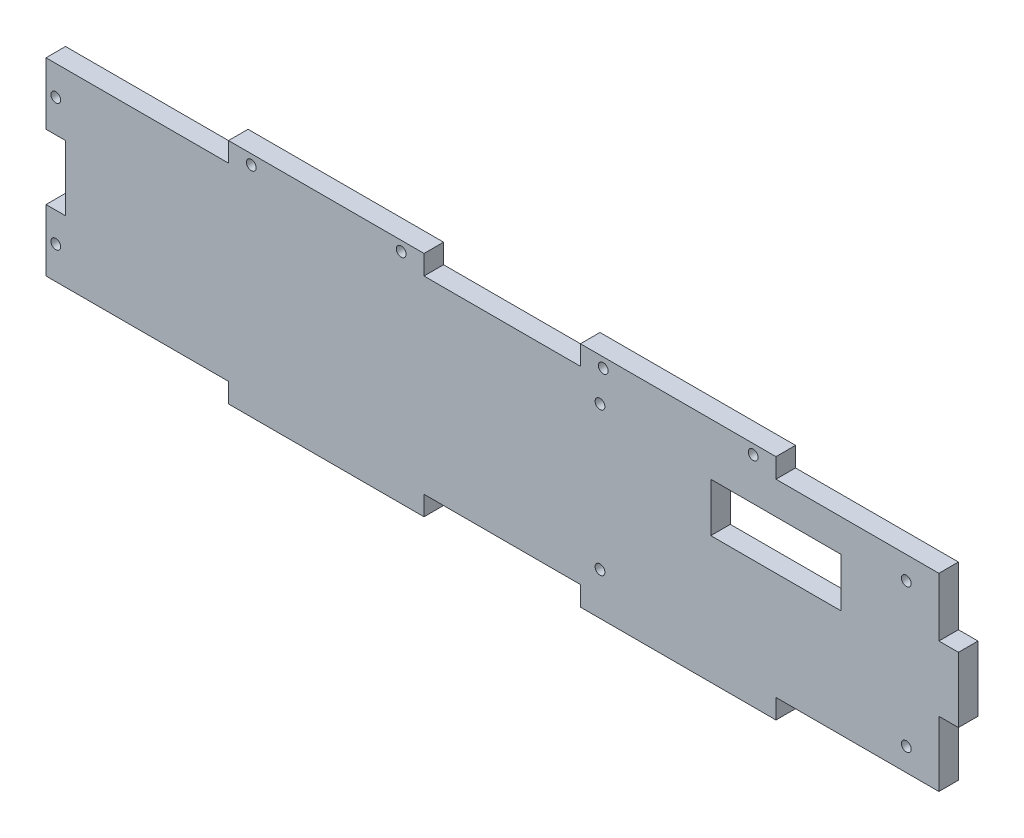
SolidWorks part; units mm, degrees
ref_plane "Plan de face" through (0, 0, 0) normal (0, 0, 1) x (1, 0, 0)
ref_plane "Plan de dessus" through (0, 0, 0) normal (0, 1, 0) x (1, 0, 0)
ref_plane "Plan de droite" through (0, 0, 0) normal (1, 0, 0) x (0, 0, -1)
sketch "Esquisse1" plane through (0, 0, 0) normal (0, 0, 1) x (1, 0, 0)
  line L1 (0, 0) -> (-268, 0)
  line L2 (0, 0) -> (0, 70)
  line L3 (0, 70) -> (-268, 70)
  line L4 (-268, 0) -> (-268, 70)
  dimension "D1" = 70
  dimension "D2" = 268
extrude "Boss.-Extru.1" add sketch "Esquisse1" along normal blind 6
sketch "Esquisse2" plane through (0, 0, 6) normal (0, 0, 1) x (1, 0, 0)
  line L0 (-268, 0) -> (0, 0) construction
  line L1 (-268, 0) -> (-218, 0)
  line L2 (-268, 0) -> (-268, 6)
  line L3 (-268, 6) -> (-218, 6)
  line L4 (-218, 0) -> (-218, 6)
  line L5 (0, 0) -> (-50, 0)
  line L6 (0, 0) -> (0, 6)
  line L7 (0, 6) -> (-50, 6)
  line L8 (-50, 0) -> (-50, 6)
  line L9 (-158, 0) -> (-110, 0)
  line L10 (-158, 0) -> (-158, 6)
  line L11 (-158, 6) -> (-110, 6)
  line L12 (-110, 0) -> (-110, 6)
  line L13 (0, 70) -> (-268, 70) construction
  line L14 (-268, 70) -> (-218, 70)
  line L15 (-268, 70) -> (-268, 64)
  line L16 (-268, 64) -> (-218, 64)
  line L17 (-218, 70) -> (-218, 64)
  line L18 (-158, 70) -> (-110, 70)
  line L19 (-158, 70) -> (-158, 64)
  line L20 (-158, 64) -> (-110, 64)
  line L21 (-110, 70) -> (-110, 64)
  line L23 (0, 70) -> (-50, 70)
  line L24 (0, 70) -> (0, 64)
  line L25 (0, 64) -> (-50, 64)
  line L26 (-50, 70) -> (-50, 64)
  dimension "D1" = 6
  dimension "D2" = 6
  dimension "D3" = 6
  dimension "D4" = 50
  dimension "D5" = 60
  dimension "D6" = 60
  dimension "D7" = 50
  dimension "D8" = 6
  dimension "D9" = 6
  dimension "D10" = 6
  dimension "D11" = 50
  dimension "D12" = 60
  dimension "D13" = 50
  dimension "D14" = 60
extrude "Enlèv. mat.-Extru.1" cut sketch "Esquisse2" against normal through all
sketch "Esquisse3" plane through (0, 0, 0) normal (1, 0, 0) x (0, 0, -1)
  line L0 (-6, 6) -> (-6, 64) construction
  line L1 (-6, 46) -> (0, 46)
  line L2 (-6, 46) -> (-6, 26)
  line L3 (-6, 26) -> (0, 26)
  line L4 (0, 46) -> (0, 26)
  line L5 (0, 6) -> (0, 64) construction
  line L8 (0, 6) -> (-6, 6) construction
  dimension "D1" = 20
  dimension "D2" = 20
extrude "Boss.-Extru.2" add sketch "Esquisse3" along normal blind 6
sketch "Esquisse4" plane through (0, 0, 6) normal (0, 0, 1) x (1, 0, 0)
  line L0 (-218, 6) -> (-268, 6) construction
  line L1 (-50, 64) -> (0, 64) construction
  line L2 (0, 46) -> (0, 64) construction
  line L3 (-70, 54) -> (-30, 54)
  line L4 (-70, 54) -> (-70, 39)
  line L5 (-70, 39) -> (-30, 39)
  line L6 (-30, 54) -> (-30, 39)
  circle A0 centre (-104, 57) radius 1.5
  circle A1 centre (-104, 13) radius 1.5
  circle A2 centre (-10, 57) radius 1.5
  circle A3 centre (-10, 13) radius 1.5
  dimension "D1" = 44
  dimension "D2" = 94
  dimension "D3" = 0
  dimension "D4" = 0
  dimension "D5" = 7
  dimension "D6" = 10
  dimension "D7" = 0
  dimension "D8" = 15
  dimension "D9" = 40
  dimension "D10" = 10
  dimension "D11" = 30
extrude "Enlèv. mat.-Extru.2" cut sketch "Esquisse4" against normal blind 10
sketch "Esquisse5" plane through (-268, 0, 0) normal (-1, 0, 0) x (0, 0, 1)
  line L0 (6, 64) -> (6, 6) construction
  line L1 (0, 64) -> (6, 64)
  line L2 (0, 64) -> (0, 45)
  line L3 (0, 45) -> (6, 45)
  line L4 (6, 64) -> (6, 45)
  line L5 (0, 64) -> (0, 6) construction
  line L6 (6, 6) -> (0, 6)
  line L7 (6, 6) -> (6, 25)
  line L8 (6, 25) -> (0, 25)
  line L9 (0, 6) -> (0, 25)
  dimension "D1" = 20
  dimension "D2" = 19
extrude "Boss.-Extru.3" add sketch "Esquisse5" along normal blind 6
sketch "Esquisse6" plane through (0, 0, 0) normal (0, 0, -1) x (-1, 0, 0)
  line L0 (274, 25) -> (274, 6) construction
  line L1 (218, 6) -> (274, 6) construction
  line L2 (274, 64) -> (274, 45) construction
  line L3 (274, 45) -> (268, 45) construction
  line L4 (158, 70) -> (218, 70) construction
  line L5 (218, 64) -> (218, 70) construction
  line L6 (158, 70) -> (158, 64) construction
  line L7 (110, 64) -> (110, 70) construction
  line L8 (50, 70) -> (110, 70) construction
  line L9 (50, 70) -> (50, 64) construction
  circle A0 centre (271, 16) radius 1.5
  circle A1 centre (271, 55) radius 1.5
  circle A2 centre (211, 67) radius 1.5
  circle A3 centre (165, 67) radius 1.5
  circle A4 centre (103, 67) radius 1.5
  circle A5 centre (57, 67) radius 1.5
  point P22 (218, 67)
  point P25 (158, 67)
  dimension "D1" = 3
  dimension "D2" = 3
  dimension "D3" = 10
  dimension "D4" = 3
  dimension "D5" = 3
  dimension "D6" = 10
  dimension "D7" = 3
  dimension "D8" = 3
  dimension "D9" = 7
  dimension "D10" = 3
  dimension "D11" = 7
  dimension "D12" = 3
  dimension "D13" = 7
  dimension "D14" = 3
  dimension "D15" = 3
  dimension "D16" = 3
  dimension "D17" = 3
  dimension "D18" = 7
extrude "Enlèv. mat.-Extru.3" cut sketch "Esquisse6" against normal through all
sketch "Esquisse7" plane through (0, 0, 0) normal (0, 0, -1) x (-1, 0, 0)
  circle A0 centre (271, 16) radius 2.995
  circle A1 centre (271, 55) radius 2.995
  circle A2 centre (211, 67) radius 2.995
  circle A3 centre (165, 67) radius 2.995
  circle A4 centre (103, 67) radius 2.995
  circle A5 centre (57, 67) radius 2.995
  circle A6 centre (104, 57) radius 3
  circle A7 centre (104, 13) radius 3
  circle A8 centre (10, 13) radius 3
  circle A9 centre (10, 57) radius 3
  dimension "D1" = 6
  dimension "D2" = 5.99
  dimension "D3" = 5.99
  dimension "D4" = 5.99
  dimension "D5" = 5.99
  dimension "D6" = 5.99
  dimension "D7" = 5.99
  dimension "D8" = 6
  dimension "D9" = 6
  dimension "D10" = 6
extrude "Enlèv. mat.-Extru.4" cut sketch "Esquisse7" against normal blind 3
